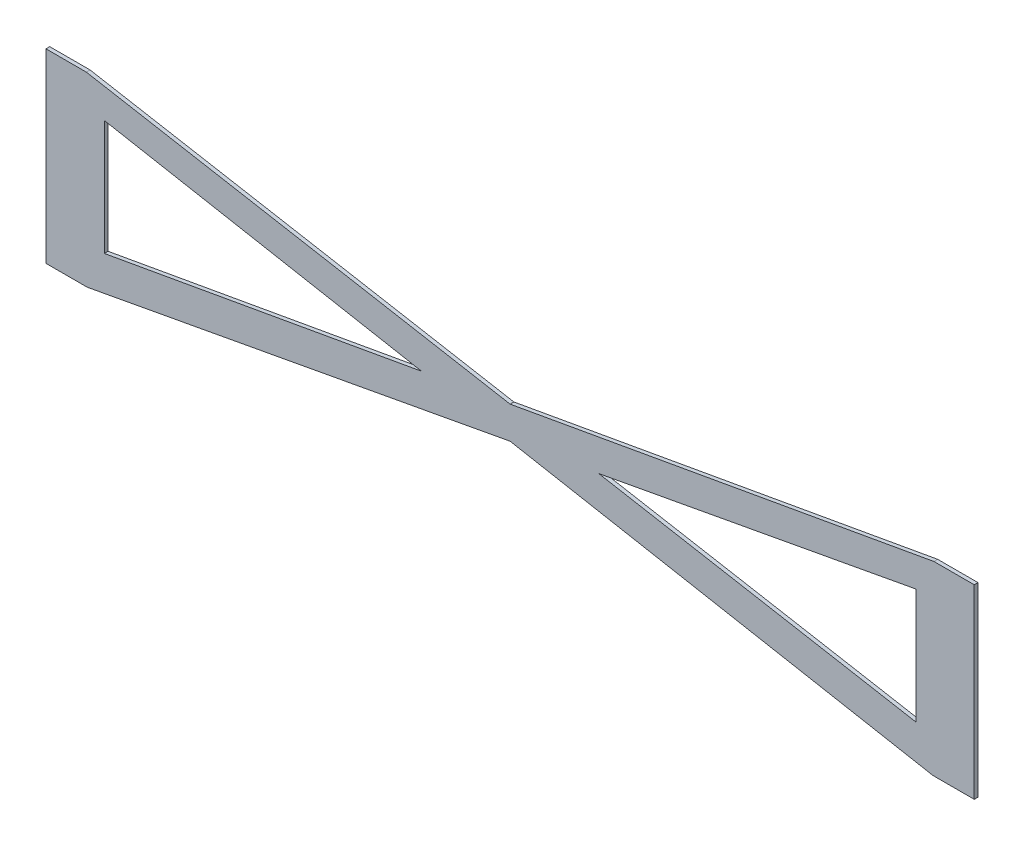
SolidWorks part; units mm, degrees
ref_plane "Front Plane" through (0, 0, 0) normal (0, 0, 1) x (1, 0, 0)
ref_plane "Top Plane" through (0, 0, 0) normal (0, 1, 0) x (1, 0, 0)
ref_plane "Right Plane" through (0, 0, 0) normal (1, 0, 0) x (0, 0, -1)
sketch "Sketch1" plane through (0, 0, 0) normal (0, 0, 1) x (1, 0, 0)
  line L0 (0, 0) -> (246.998, 49.45) construction
  line L1 (0, 0) -> (10.9854, 0)
  line L2 (0, 0) -> (0, 49.45)
  line L3 (0, 49.45) -> (10.7305, 49.45)
  line L4 (246.998, 0) -> (246.998, 49.45)
  line L5 (246.998, 0) -> (0, 49.45) construction
  line L6 (15.5, 40.7057) -> (99.9299, 25.1203)
  line L7 (10.7305, 49.45) -> (123.499, 29.3262)
  line L8 (236.2675, 49.45) -> (123.499, 29.3262)
  line L9 (231.498, 40.7057) -> (147.0681, 25.1203)
  line L10 (236.2675, 49.45) -> (246.998, 49.45)
  line L12 (15.5, 10.0536) -> (15.5, 40.7057)
  line L14 (231.498, 10.0536) -> (231.498, 40.7057)
  line L16 (236.0126, 0) -> (246.998, 0)
  line L17 (123.499, 20.7695) -> (236.0126, 0)
  line L18 (99.9299, 25.1203) -> (15.5, 10.0536)
  line L19 (147.0681, 25.1203) -> (231.498, 10.0536)
  line L20 (123.499, 20.7695) -> (10.9854, 0)
  dimension "D1" = 246.998
  dimension "D2" = 49.45
  dimension "D3" = 15.5
extrude "Boss-Extrude1" add sketch "Sketch1" along normal blind 1
